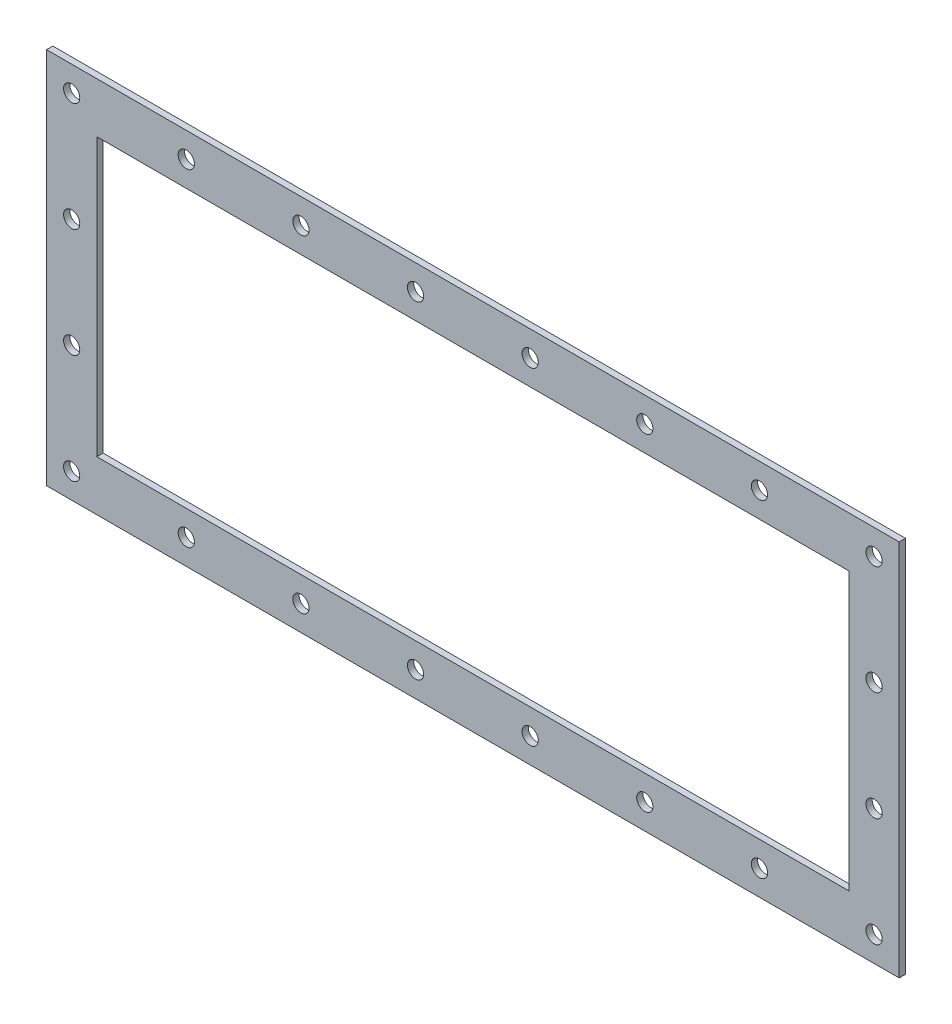
SolidWorks part; units mm, degrees
material "Silicon Rubber"
ref_plane "Front Plane" through (0, 0, 0) normal (0, 0, 1) x (1, 0, 0)
ref_plane "Top Plane" through (0, 0, 0) normal (0, 1, 0) x (1, 0, 0)
ref_plane "Right Plane" through (0, 0, 0) normal (1, 0, 0) x (0, 0, -1)
sketch "Sketch1" plane through (0, 0, 0) normal (0, 0, 1) x (1, 0, 0)
  line L1 (-53.85, -23.85) -> (53.85, -23.85)
  line L2 (-53.85, -23.85) -> (-53.85, 23.85)
  line L3 (-53.85, 23.85) -> (53.85, 23.85)
  line L4 (53.85, -23.85) -> (53.85, 23.85)
  line L5 (-53.85, -23.85) -> (53.85, 23.85) construction
  line L6 (-53.85, 23.85) -> (53.85, -23.85) construction
  line L7 (-50.675, 20.675) -> (50.675, 20.675) construction
  line L8 (-50.675, 20.675) -> (-50.675, -20.675) construction
  line L9 (-50.675, -20.675) -> (50.675, -20.675) construction
  line L10 (50.675, 20.675) -> (50.675, -20.675) construction
  line L11 (-47.5, 17.5) -> (47.5, 17.5)
  line L12 (-47.5, 17.5) -> (-47.5, -17.5)
  line L13 (-47.5, -17.5) -> (47.5, -17.5)
  line L14 (47.5, 17.5) -> (47.5, -17.5)
  circle A0 centre (-50.675, 20.675) radius 1.025
  circle A1 centre (50.675, 20.675) radius 1.025
  circle A2 centre (-50.675, -20.675) radius 1.025
  circle A3 centre (50.675, -20.675) radius 1.025
  circle A4 centre (-7.2393, 20.675) radius 1.025
  circle A5 centre (-7.2393, -20.675) radius 1.025
  circle A8 centre (-36.1964, 20.675) radius 1.025
  circle A9 centre (-21.7179, 20.675) radius 1.025
  circle A10 centre (7.2393, 20.675) radius 1.025
  circle A11 centre (21.7179, 20.675) radius 1.025
  circle A12 centre (-50.675, 6.8917) radius 1.025
  circle A13 centre (-50.675, -6.8917) radius 1.025
  circle A14 centre (50.675, 6.8917) radius 1.025
  circle A15 centre (50.675, -6.8917) radius 1.025
  circle A16 centre (7.2393, -20.675) radius 1.025
  circle A17 centre (21.7179, -20.675) radius 1.025
  circle A18 centre (-21.7179, -20.675) radius 1.025
  circle A19 centre (-36.1964, -20.675) radius 1.025
  circle A20 centre (36.1964, 20.675) radius 1.025
  circle A21 centre (36.1964, -20.675) radius 1.025
  point P0 (0, 0)
  dimension "D7" = 2.05
  dimension "D1" = 107.7
  dimension "D2" = 47.7
  dimension "D3" = 3.175
  dimension "D4" = 3.175
  dimension "D5" = 3.175
  dimension "D6" = 3.175
  dimension "D8" = 41.35
  dimension "D9" = 13.7833
  dimension "D10" = 13.7833
  dimension "D11" = 101.35
  dimension "D12" = 14.4786
  dimension "D13" = 14.4786
  dimension "D14" = 14.4786
  dimension "D15" = 14.4786
  dimension "D16" = 6.35
  dimension "D17" = 6.35
  dimension "D18" = 6.35
  dimension "D19" = 6.35
  dimension "D20" = 14.4786
  dimension "D21" = 14.4786
extrude "Boss-Extrude1" add sketch "Sketch1" along normal blind 0.7937 contours L1 L4 L3 L2 A19 A18 A17 A16 A15 A14 A13 A12 A11 A10 A9 A8 A5 A4 A3 A2 A1 A0 | L12 L11 L14 L13
